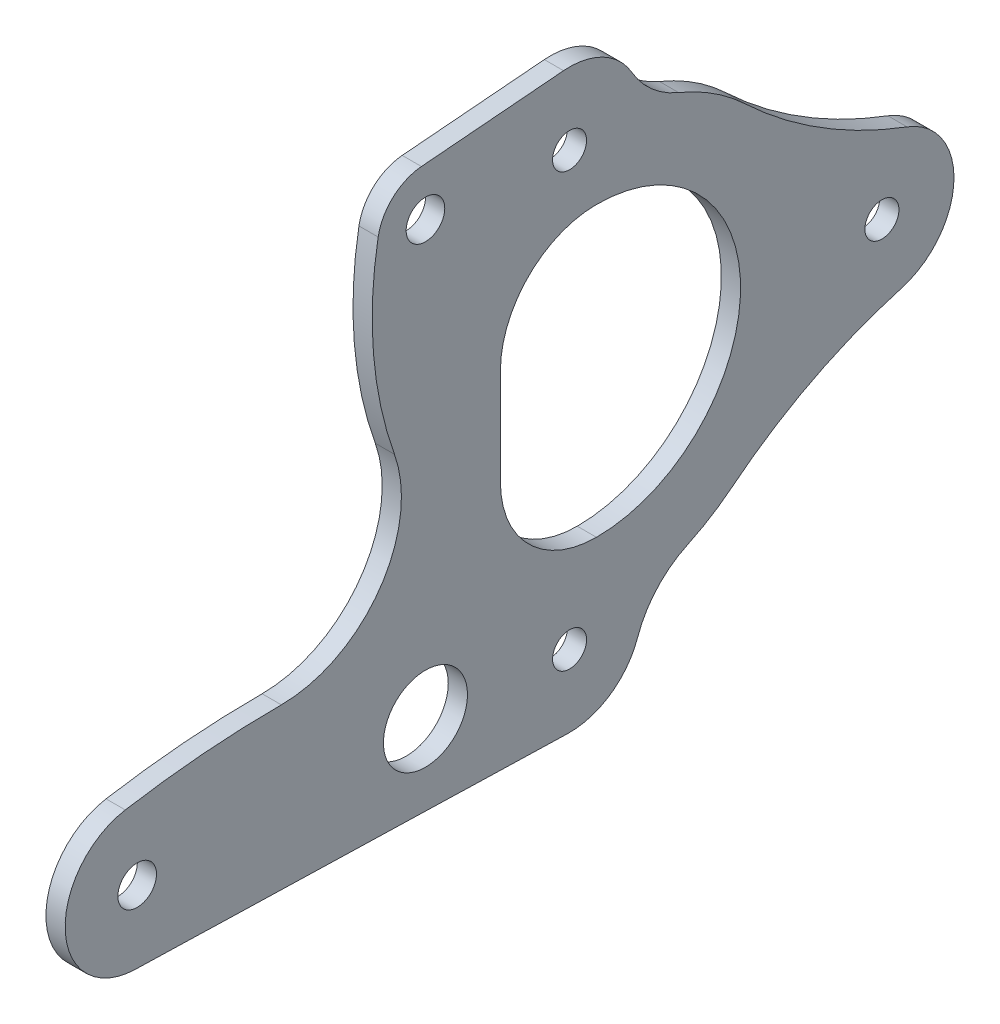
SolidWorks part; units mm, degrees
ref_plane "Front" through (0, 0, 0) normal (0, 0, 1) x (1, 0, 0)
ref_plane "Top" through (0, 0, 0) normal (0, 1, 0) x (1, 0, 0)
ref_plane "Right" through (0, 0, 0) normal (1, 0, 0) x (0, 0, -1)
sketch "Sketch1" plane through (0, 0, 0) normal (1, 0, 0) x (0, 0, -1)
  line L0 (-19.3145, -36.5088) -> (37.8355, -38.0963)
  line L5 (18.519, 36.4903) -> (37.3035, 38.0666)
  line L6 (28.956, 7.874) -> (28.956, -4.826)
  circle A0 centre (0, 0) radius 14.2875 construction
  circle A1 centre (0, 0) radius 14.2875 construction
  arc A2 (46.3448, 33.3445) -> (37.3035, 38.0666) centre (38.1, 28.575) ccw
  arc A4 (53.7234, -24.3779) -> (59.5553, -20.7503) centre (41.656, 1.524) ccw
  arc A5 (81.9891, -9.1629) -> (82.7196, 8.9232) centre (79.3877, 0) ccw
  arc A6 (37.8355, -38.0963) -> (47.0943, -31.7099) centre (38.1, -28.575) ccw
  arc A9 (12.7984, 31.2761) -> (14.955, 5.3256) centre (62.8112, 22.3676) ccw
  arc A10 (81.9891, -9.1629) -> (59.5553, -20.7503) centre (99.3316, -70.2488) ccw
  arc A11 (53.7234, -24.3779) -> (47.0943, -31.7099) centre (59.0868, -35.8898) ccw
  arc A12 (46.3448, 33.3445) -> (52.5127, 27.9562) centre (57.338, 39.7039) ccw
  arc A13 (61.2934, 22.2822) -> (82.7196, 8.9232) centre (104.9321, 68.4115) ccw
  arc A14 (61.2934, 22.2822) -> (52.5127, 27.9562) centre (41.656, 1.524) ccw
  arc A15 (28.956, 7.874) -> (41.656, 20.574) centre (41.656, 7.874) cw
  arc A16 (41.656, -17.526) -> (28.956, -4.826) centre (41.656, -4.826) cw
  arc A17 (-20.6266, -17.5939) -> (-19.3145, -36.5088) centre (-19.05, -26.9875) ccw
  circle A18 centre (-19.05, -26.9875) radius 2.0193 construction
  arc A19 (0, -15.875) -> (-20.6266, -17.5939) centre (0, -140.4938) ccw
  arc A20 (0, -15.875) -> (14.955, 5.3256) centre (0, 0) ccw
  circle A21 centre (0, 0) radius 15.875 construction
  arc A24 (41.656, -17.526) -> (41.656, 20.574) centre (41.656, 1.524) ccw
  circle A25 centre (41.656, 1.524) radius 2.0193 construction
  arc A27 (18.519, 36.4903) -> (12.7984, 31.2761) centre (19.05, 30.1625) ccw
  circle A30 centre (19.05, -26.9875) radius 5.5562 construction
  circle A31 centre (19.05, -26.9875) radius 2.4892 construction
  circle A33 centre (19.05, 30.1625) radius 2.0193 construction
  point P12 (0, 0)
  point P18 (0, 0)
  point P19 (0, 0)
  dimension "D2" = 50.8
  dimension "D3" = 38.1
  dimension "D4" = 9.525
  dimension "D5" = 9.525
  dimension "D6" = 12.7
  dimension "D7" = 9.525
  dimension "D8" = 127
  dimension "D9" = 12.7
  dimension "D10" = 12.7
  dimension "D12" = 12.7
  dimension "D13" = 11.1125
  dimension "D11" = 12.7
  dimension "D1" = 1.5875
extrude "Boss-Extrude1" add sketch "Sketch1" along normal blind 2.54
hole_wizard "7/16 (0.4375) Diameter Hole1" positions "Sketch2" profile "Sketch3" hole size "7/16" standard "ANSI Inch" end condition through all
sketch "Sketch2" plane through (2.54, 0, 0) normal (1, 0, 0) x (0, 0, -1)
  circle A0 centre (19.05, -26.9875) radius 2.4892 construction
  point P2 (19.05, -26.9875)
  point P19 (0, 0)
sketch "Sketch3" plane through (2.54, -26.9875, -19.05) normal (0, 1, 0) x (0, 0, -1)
  line L0 (0, 0) -> (0, 2.54)
  line L1 (0, 2.54) -> (5.5562, 2.54)
  line L2 (5.5562, 2.54) -> (5.5562, 0)
  line L5 (5.5562, 0) -> (0, 0)
  line L11 (0, -6.35) -> (0, 107.95) construction
  dimension "Thru Hole Dia." = 11.1125
  dimension "Thru Hole Depth" = 2.54
hole_wizard "#8 Clearance Hole2" positions "Sketch4" profile "Sketch5" hole size "#8" standard "ANSI Inch" end condition through all
sketch "Sketch4" plane through (2.54, 0, 0) normal (1, 0, 0) x (0, 0, -1)
  point P0 (38.1, -28.575)
  point P2 (79.3877, 0)
  point P4 (38.1, 28.575)
sketch "Sketch5" plane through (2.54, -28.575, -38.1) normal (0, 1, 0) x (0, 0, -1)
  line L0 (0, 0) -> (0, 2.54)
  line L1 (0, 2.54) -> (2.2479, 2.54)
  line L2 (2.2479, 2.54) -> (2.2479, 0)
  line L5 (2.2479, 0) -> (0, 0)
  line L11 (0, -6.35) -> (0, 107.95) construction
  dimension "Thru Hole Dia." = 4.4958
  dimension "Thru Hole Depth" = 2.54
hole_wizard "#10 Clearance Hole2" positions "Sketch6" profile "Sketch7" hole size "#10" standard "ANSI Inch" end condition through all
sketch "Sketch6" plane through (2.54, 0, 0) normal (1, 0, 0) x (0, 0, -1)
  circle A0 centre (19.05, 30.1625) radius 2.0193 construction
  point P0 (-19.05, -26.9875)
  point P2 (19.05, 30.1625)
sketch "Sketch7" plane through (2.54, -26.9875, 19.05) normal (0, 1, 0) x (0, 0, -1)
  line L0 (0, 0) -> (0, 2.54)
  line L1 (0, 2.54) -> (2.5527, 2.54)
  line L2 (2.5527, 2.54) -> (2.5527, 0)
  line L5 (2.5527, 0) -> (0, 0)
  line L11 (0, -6.35) -> (0, 107.95) construction
  dimension "Thru Hole Dia." = 5.1054
  dimension "Thru Hole Depth" = 2.54
